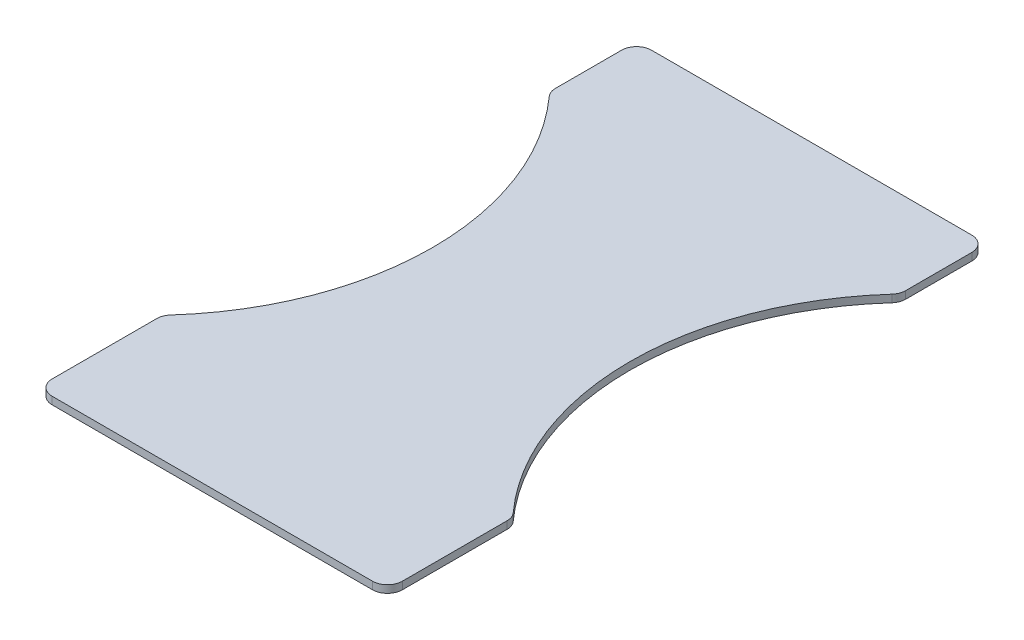
SolidWorks part; units mm, degrees
ref_plane "Front Plane" through (0, 0, 0) normal (0, 0, 1) x (1, 0, 0)
ref_plane "Top Plane" through (0, 0, 0) normal (0, 1, 0) x (1, 0, 0)
ref_plane "Right Plane" through (0, 0, 0) normal (1, 0, 0) x (0, 0, -1)
sketch "Sketch2" plane through (0, 0, 0) normal (0, 1, 0) x (1, 0, 0)
  line L0 (-59.3725, 122.1027) -> (-59.3725, 151.5847)
  line L1 (59.3725, 122.1027) -> (59.3725, 151.5847)
  line L2 (59.3725, -51.6153) -> (-59.3725, -51.6153)
  line L3 (59.3725, -51.6153) -> (59.3725, -9.103)
  line L4 (59.3725, 151.5847) -> (-59.3725, 151.5847)
  line L5 (-59.3725, -51.6153) -> (-59.3725, -9.103)
  arc A0 (-59.3725, -9.103) -> (-59.3725, 122.1027) centre (-129.4765, 56.4999) ccw
  arc A1 (59.3725, 122.1027) -> (59.3725, -9.103) centre (129.4765, 56.4999) ccw
  dimension "D3" = 192.024
  dimension "D4" = 192.024
  dimension "D1" = 118.745
  dimension "D2" = 203.2
  dimension "D5" = 59.3725
  dimension "D6" = 70.104
  dimension "D7" = 70.104
extrude "Boss-Extrude1" add sketch "Sketch2" along normal blind 2.54
sketch "Sketch3" plane through (0, 2.54, 0) normal (0, 1, 0) x (1, 0, 0)
  line L0 (59.3725, 151.5847) -> (-59.3725, 151.5847) construction
  line L1 (-38.1, -18.5233) -> (5.08, -18.5233)
  line L2 (-38.1, -18.5233) -> (-38.1, -36.3033)
  line L3 (-38.1, -36.3033) -> (5.08, -36.3033)
  line L4 (5.08, -18.5233) -> (5.08, -36.3033)
  line L5 (18.034, -12.7) -> (38.034, -12.7)
  line L6 (18.034, -12.7) -> (18.034, -42.7)
  line L7 (18.034, -42.7) -> (38.034, -42.7)
  line L8 (38.034, -12.7) -> (38.034, -42.7)
  line L9 (-37.465, 146.5047) -> (37.465, 146.5047)
  line L10 (-37.465, 146.5047) -> (-37.465, 133.8047)
  line L15 (-13.535, 7.4615) -> (11.0831, 7.4615)
  line L16 (-13.535, 7.4615) -> (-13.535, -5.9874)
  line L17 (-13.535, -5.9874) -> (11.0831, -5.9874)
  line L18 (11.0831, 7.4615) -> (11.0831, -5.9874)
  line L19 (-37.465, 133.8047) -> (37.465, 133.8047)
  line L20 (37.465, 146.5047) -> (37.465, 133.8047)
  point P19 (0, 151.5847)
  point P22 (-28.7047, 149.379)
  point P23 (0, 0)
  dimension "D1" = 43.18
  dimension "D2" = 17.78
  dimension "D3" = 20
  dimension "D4" = 30
  dimension "D5" = 38.1
  dimension "D6" = 18.034
  dimension "D7" = 12.7
  dimension "D8" = 74.93
  dimension "D9" = 12.7
  dimension "D10" = 37.465
  dimension "D11" = 5.08
fillet "Fillet3" radius 5.08 1 edges at (-59.3725, 1.27, -151.5847)
fillet "Fillet4" radius 5.08 1 edges at (59.3725, 1.27, -151.5847)
fillet "Fillet5" radius 5.08 1 edges at (-59.3725, 1.27, -122.1027)
fillet "Fillet6" radius 5.08 1 edges at (59.3725, 1.27, -122.1027)
fillet "Fillet7" radius 5.08 1 edges at (-59.3725, 1.27, 9.103)
fillet "Fillet8" radius 5.08 1 edges at (59.3725, 1.27, 9.103)
fillet "Fillet9" radius 5.08 1 edges at (59.3725, 1.27, 51.6153)
fillet "Fillet10" radius 5.08 1 edges at (-59.3725, 1.27, 51.6153)
sketch "Sketch5" plane through (0, 2.54, 0) normal (0, 1, 0) x (1, 0, 0)
  line L0 (-59.3725, -11.0794) -> (-59.3725, -46.5353) construction
  line L1 (-59.3725, -24.2013) -> (-46.5782, -24.2013)
  line L2 (-59.3725, -24.2013) -> (-59.3725, -33.2795)
  line L3 (-59.3725, -33.2795) -> (-46.5782, -33.2795)
  line L4 (-46.5782, -24.2013) -> (-46.5782, -33.2795)
  line L5 (59.3725, -46.5353) -> (59.3725, -11.0794) construction
  line L6 (59.3725, -24.2013) -> (47.3245, -24.2013)
  line L7 (59.3725, -24.2013) -> (59.3725, -33.2795)
  line L8 (59.3725, -33.2795) -> (47.3245, -33.2795)
  line L9 (47.3245, -24.2013) -> (47.3245, -33.2795)
  line L15 (-16.982, 118.7) -> (17.018, 118.7)
  line L16 (-16.982, 118.7) -> (-16.982, 12.7)
  line L17 (-16.982, 12.7) -> (17.018, 12.7)
  line L18 (17.018, 118.7) -> (17.018, 12.7)
  dimension "D1" = 106
  dimension "D2" = 34
  dimension "D3" = 12.7
  dimension "D4" = 17.018
sketch "Sketch6" plane through (0, 0, 0) normal (0, -1, 0) x (1, 0, 0)
  circle A0 centre (0, -111.1208) radius 10.0395
  dimension "D1" = 20.079
